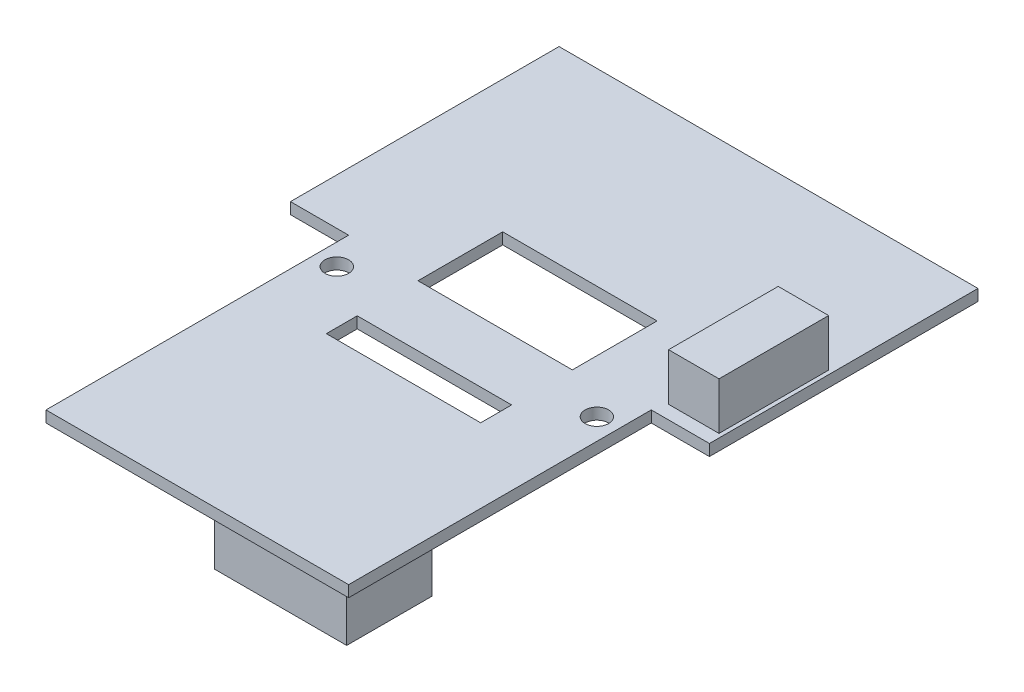
SolidWorks part; units mm, degrees
ref_plane "前视基准面" through (0, 0, 0) normal (0, 0, 1) x (1, 0, 0)
ref_plane "上视基准面" through (0, 0, 0) normal (0, 1, 0) x (1, 0, 0)
ref_plane "右视基准面" through (0, 0, 0) normal (1, 0, 0) x (0, 0, -1)
other "Configuration Table"
sketch "草图1" plane through (0, 0, 0) normal (0, 1, 0) x (1, 0, 0)
  line L0 (0, 24.0223) -> (0, -38.3661) construction
  line L1 (16, 0) -> (16, -32)
  line L2 (16, -32) -> (-16, -32)
  line L3 (16, 0) -> (22.15, 0)
  line L4 (22.15, 0) -> (22.15, 28.4)
  line L5 (22.15, 28.4) -> (-22.15, 28.4)
  line L6 (-22.15, 0) -> (-22.15, 28.4)
  line L7 (-16, 0) -> (-22.15, 0)
  line L8 (-16, 0) -> (-16, -32)
  line L10 (-8.1618, 8.4545) -> (8.1618, 8.4545)
  line L11 (-8.1618, 8.4545) -> (-8.1618, -0.5067)
  line L12 (-8.1618, -0.5067) -> (8.1618, -0.5067)
  line L13 (8.1618, 8.4545) -> (8.1618, -0.5067)
  line L14 (-8.1618, 8.4545) -> (8.1618, -0.5067) construction
  line L15 (-8.1618, -0.5067) -> (8.1618, 8.4545) construction
  line L16 (-8.1618, -10.1977) -> (8.1618, -10.1977)
  line L17 (-8.1618, -10.1977) -> (-8.1618, -6.9278)
  line L18 (-8.1618, -6.9278) -> (8.1618, -6.9278)
  line L19 (8.1618, -10.1977) -> (8.1618, -6.9278)
  line L20 (-8.1618, -10.1977) -> (8.1618, -6.9278) construction
  line L21 (-8.1618, -6.9278) -> (8.1618, -10.1977) construction
  circle A0 centre (13.75, -3.5) radius 1.25
  circle A1 centre (-13.75, -3.5) radius 1.25
  point P10 (0, 28.4)
  point P11 (0, -32)
  point P17 (0, 3.9739)
  point P22 (8.0702, -11.665)
  point P23 (0, -8.5627)
  point P24 (0, -8.5627)
  dimension "D5" = 2.5
  dimension "D6" = 27.5
  dimension "D7" = 3.5
  dimension "D1" = 32
  dimension "D2" = 44.3
  dimension "D3" = 32
  dimension "D4" = 28.4
extrude "凸台-拉伸1" add sketch "草图1" along normal blind 1.2
sketch "草图2" plane through (0, 1.2, 0) normal (0, 1, 0) x (1, 0, 0)
  line L1 (21.7356, 1.4291) -> (16.4015, 1.4291)
  line L2 (21.7356, 1.4291) -> (21.7356, 13.0213)
  line L3 (21.7356, 13.0213) -> (16.4015, 13.0213)
  line L4 (16.4015, 1.4291) -> (16.4015, 13.0213)
extrude "凸台-拉伸2" add sketch "草图2" along normal blind 5
sketch "草图3" plane through (0, 0, 0) normal (0, -1, 0) x (1, 0, 0)
  line L1 (15.2675, 31.4727) -> (1.2675, 31.4727)
  line L2 (15.2675, 31.4727) -> (15.2675, 22.4727)
  line L3 (15.2675, 22.4727) -> (1.2675, 22.4727)
  line L4 (1.2675, 31.4727) -> (1.2675, 22.4727)
  dimension "D1" = 14
  dimension "D2" = 9
extrude "凸台-拉伸3" add sketch "草图3" along normal blind 5
